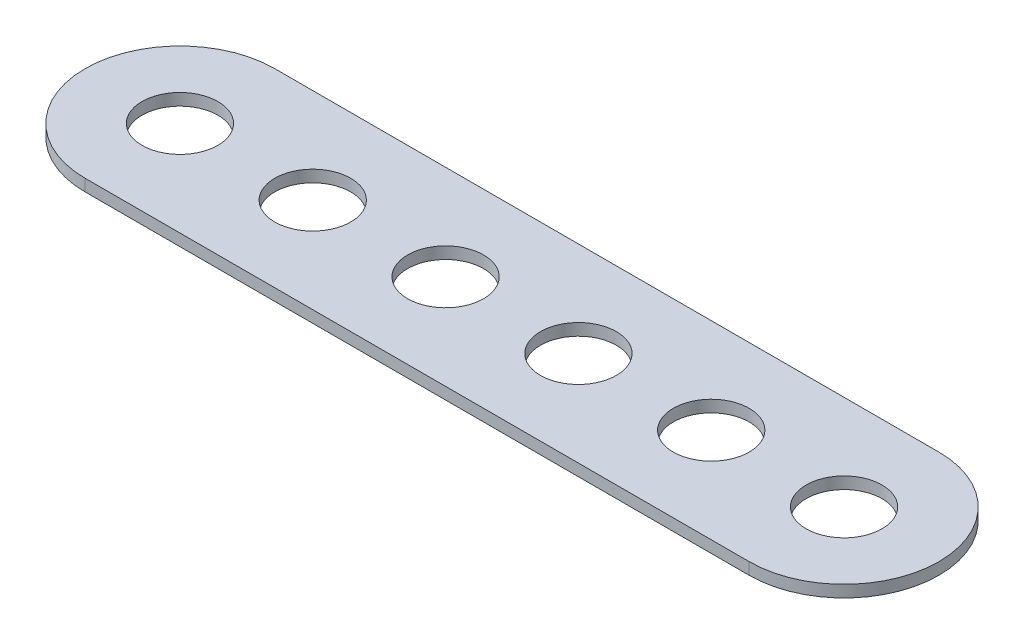
SolidWorks part; units mm, degrees
ref_plane "Front Plane" through (0, 0, 0) normal (0, 0, 1) x (1, 0, 0)
ref_plane "Top Plane" through (0, 0, 0) normal (0, 1, 0) x (1, 0, 0)
ref_plane "Right Plane" through (0, 0, 0) normal (1, 0, 0) x (0, 0, -1)
sketch "Sketch1" plane through (0, 0, 0) normal (0, 1, 0) x (1, 0, 0)
  line L0 (0, 0) -> (-177.8, 0) construction
  line L1 (0, 25.4) -> (-177.8, 25.4)
  line L2 (0, -25.4) -> (-177.8, -25.4)
  arc A0 (0, -25.4) -> (0, 25.4) centre (0, 0) ccw
  arc A1 (-177.8, 25.4) -> (-177.8, -25.4) centre (-177.8, 0) ccw
  dimension "D1" = 50.8
  dimension "D2" = 177.8
extrude "Boss-Extrude1" add sketch "Sketch1" along normal blind 3.175
sketch "Sketch3" plane through (0, 3.175, 0) normal (0, 1, 0) x (1, 0, 0)
  circle A1 centre (-177.8, 0) radius 10.16
  dimension "D1" = 20.32
extrude "Cut-Extrude1" cut sketch "Sketch3" against normal through all
pattern_linear "LPattern1" count 6 spacing 35.56 along (1, 0, 0) of "Cut-Extrude1"
